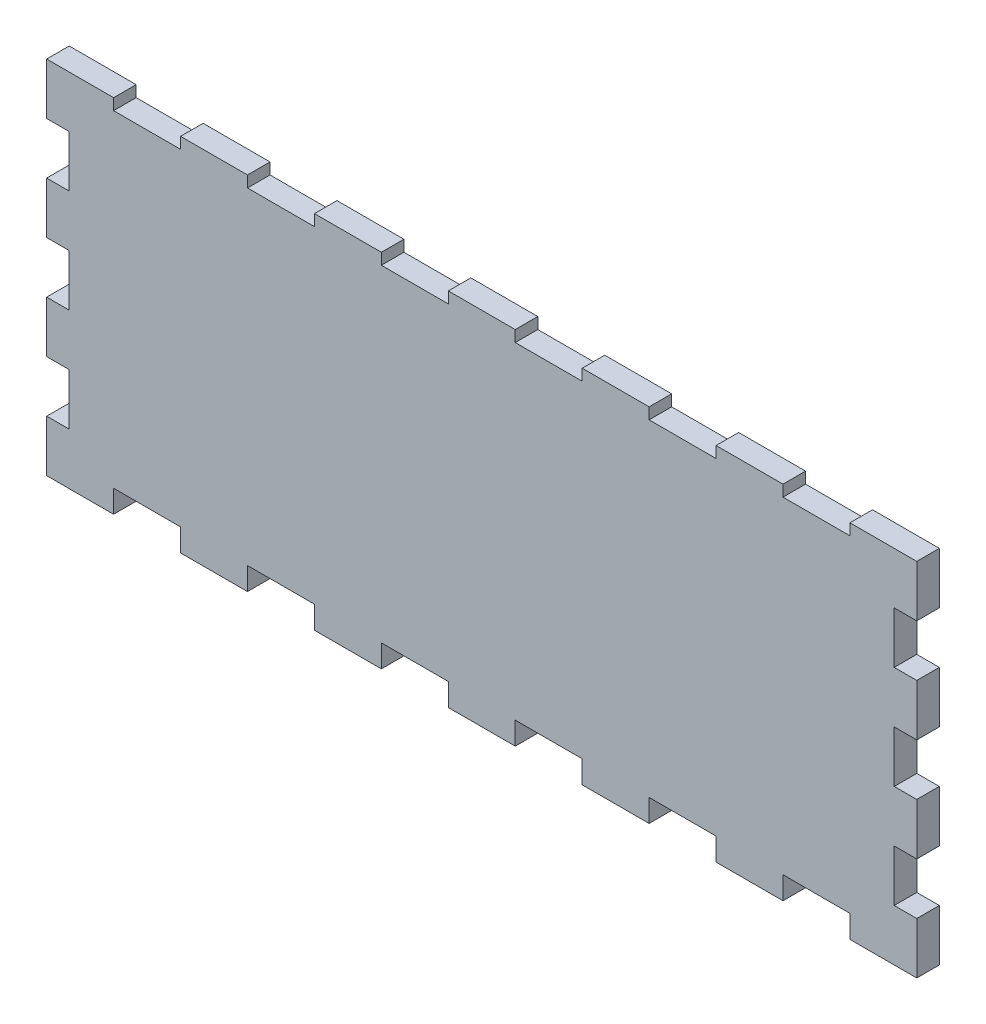
SolidWorks part; units mm, degrees
material "Balsa"
ref_plane "Front" through (0, 0, 0) normal (0, 0, 1) x (1, 0, 0)
ref_plane "Top" through (0, 0, 0) normal (0, 1, 0) x (1, 0, 0)
ref_plane "Right" through (0, 0, 0) normal (1, 0, 0) x (0, 0, -1)
sketch "Esboço1" plane through (0, 0, 0) normal (0, 0, 1) x (1, 0, 0)
  line L1 (115.75, -48) -> (-115.75, -48)
  line L2 (115.75, -48) -> (115.75, 48)
  line L3 (115.75, 48) -> (-115.75, 48)
  line L4 (-115.75, -48) -> (-115.75, 48)
  line L5 (115.75, -48) -> (-115.75, 48) construction
  line L6 (115.75, 48) -> (-115.75, -48) construction
  point P0 (0, 0)
  dimension "D1" = 231.5
  dimension "D2" = 96
extrude "Ressalto-extrusão1" add sketch "Esboço1" along normal blind 6
sketch "Esboço2" plane through (0, 0, 0) normal (0, 0, -1) x (-1, 0, 0)
  line L0 (26.7023, -42) -> (8.89, -42)
  line L1 (62.3223, -42) -> (44.51, -42)
  line L2 (62.3223, -48) -> (44.51, -48)
  line L3 (26.7023, -48) -> (8.89, -48)
  line L4 (97.9423, -48) -> (97.9423, -42)
  line L5 (80.13, -48) -> (80.13, -42)
  line L6 (-8.9177, -42) -> (-26.73, -42)
  line L7 (62.3223, -48) -> (62.3223, -42)
  line L8 (-8.9177, -48) -> (-26.73, -48)
  line L9 (44.51, -48) -> (44.51, -42)
  line L10 (-44.5377, -42) -> (-62.35, -42)
  line L11 (26.7023, -48) -> (26.7023, -42)
  line L12 (-44.5377, -48) -> (-62.35, -48)
  line L13 (8.89, -48) -> (8.89, -42)
  line L14 (-80.1577, -42) -> (-97.97, -42)
  line L15 (-8.9177, -48) -> (-8.9177, -42)
  line L16 (-80.1577, -48) -> (-97.97, -48)
  line L17 (-26.73, -48) -> (-26.73, -42)
  line L18 (-80.1577, 51) -> (-97.97, 51)
  line L19 (-44.5377, -48) -> (-44.5377, -42)
  line L20 (-62.35, 45) -> (-44.5377, 45)
  line L21 (-62.35, -48) -> (-62.35, -42)
  line L22 (-44.5377, 51) -> (-62.35, 51)
  line L23 (-80.1577, -48) -> (-80.1577, -42)
  line L24 (-26.73, 45) -> (-8.9177, 45)
  line L25 (-97.97, -48) -> (-97.97, -42)
  line L26 (-8.9177, 51) -> (-26.73, 51)
  line L27 (8.89, 45) -> (26.7023, 45)
  line L29 (80.13, 45) -> (80.13, 51)
  line L31 (62.3223, 45) -> (62.3223, 51)
  line L32 (62.3223, 51) -> (44.51, 51)
  line L33 (44.51, 45) -> (44.51, 51)
  line L34 (80.13, 45) -> (97.9423, 45)
  line L35 (26.7023, 45) -> (26.7023, 51)
  line L36 (26.7023, 51) -> (8.89, 51)
  line L37 (8.89, 45) -> (8.89, 51)
  line L38 (44.51, 45) -> (62.3223, 45)
  line L39 (-8.9177, 45) -> (-8.9177, 51)
  line L41 (-26.73, 45) -> (-26.73, 51)
  line L43 (-44.5377, 45) -> (-44.5377, 51)
  line L45 (-62.35, 45) -> (-62.35, 51)
  line L47 (-80.1577, 45) -> (-80.1577, 51)
  line L49 (-97.97, 45) -> (-97.97, 51)
  line L55 (97.9423, 45) -> (97.9423, 51)
  line L56 (97.9423, -42) -> (80.13, -42)
  line L57 (97.9423, -48) -> (80.13, -48)
  line L58 (97.9423, 51) -> (80.13, 51)
  line L59 (-97.97, 45) -> (-80.1577, 45)
  line L61 (-115.7777, -48) -> (-115.7777, -42) [skipped]
  line L62 (-115.7777, 45) -> (-115.7777, 51) [skipped]
  dimension "D1" = 6
  dimension "D3" = 7
  dimension "D4" = 2
extrude "Corte-extrusão1" cut sketch "Esboço2" against normal up to next
sketch "Esboço3" plane through (0, 0, 0) normal (0, 0, 1) x (1, 0, 0)
  line L1 (115.75, -48) -> (-115.75, -48)
  line L2 (115.75, -48) -> (115.75, 48)
  line L3 (115.75, 48) -> (-115.75, 48)
  line L4 (-115.75, -48) -> (-115.75, 48)
  line L5 (115.75, -48) -> (-115.75, 48) construction
  line L6 (115.75, 48) -> (-115.75, -48) construction
  point P0 (0, 0)
  dimension "D1" = 231.5
  dimension "D2" = 96
sketch "Esboço4" plane through (0, 0, 0) normal (0, 0, -1) x (-1, 0, 0)
  line L0 (109.75, -6.86) -> (109.75, 6.8557)
  line L3 (115.75, 34.2857) -> (109.75, 34.2857)
  line L5 (115.75, -6.86) -> (115.75, 6.8557)
  line L6 (-109.75, 34.2857) -> (-115.75, 34.2857)
  line L7 (109.75, 20.57) -> (109.75, 34.2857)
  line L8 (-109.75, 20.57) -> (-115.75, 20.57)
  line L9 (115.75, 20.57) -> (115.75, 34.2857)
  line L10 (-109.75, 6.8557) -> (-115.75, 6.8557)
  line L12 (-109.75, -6.86) -> (-115.75, -6.86)
  line L13 (-115.75, 20.57) -> (-115.75, 34.2857)
  line L14 (-109.75, -20.5743) -> (-115.75, -20.5743)
  line L15 (-109.75, 20.57) -> (-109.75, 34.2857)
  line L16 (-109.75, -34.29) -> (-115.75, -34.29)
  line L17 (-115.75, -6.86) -> (-115.75, 6.8557)
  line L18 (-109.75, -6.86) -> (-109.75, 6.8557)
  line L20 (115.75, 20.57) -> (109.75, 20.57)
  line L22 (115.75, 6.8557) -> (109.75, 6.8557)
  line L24 (115.75, -6.86) -> (109.75, -6.86)
  line L26 (115.75, -20.5743) -> (109.75, -20.5743)
  line L28 (115.75, -34.29) -> (109.75, -34.29)
  line L32 (115.75, -34.29) -> (115.75, -20.5743)
  line L33 (109.75, -34.29) -> (109.75, -20.5743)
  line L34 (-109.75, -34.29) -> (-109.75, -20.5743)
  line L35 (-115.75, -34.29) -> (-115.75, -20.5743)
  line L37 (-109.75, -48.0043) -> (-115.75, -48.0043) [skipped]
  line L49 (115.75, -48.0043) -> (109.75, -48.0043) [skipped]
  dimension "D1" = 6
  dimension "D3" = 2
  dimension "D4" = 4
extrude "Corte-extrusão3" cut sketch "Esboço4" against normal up to next
